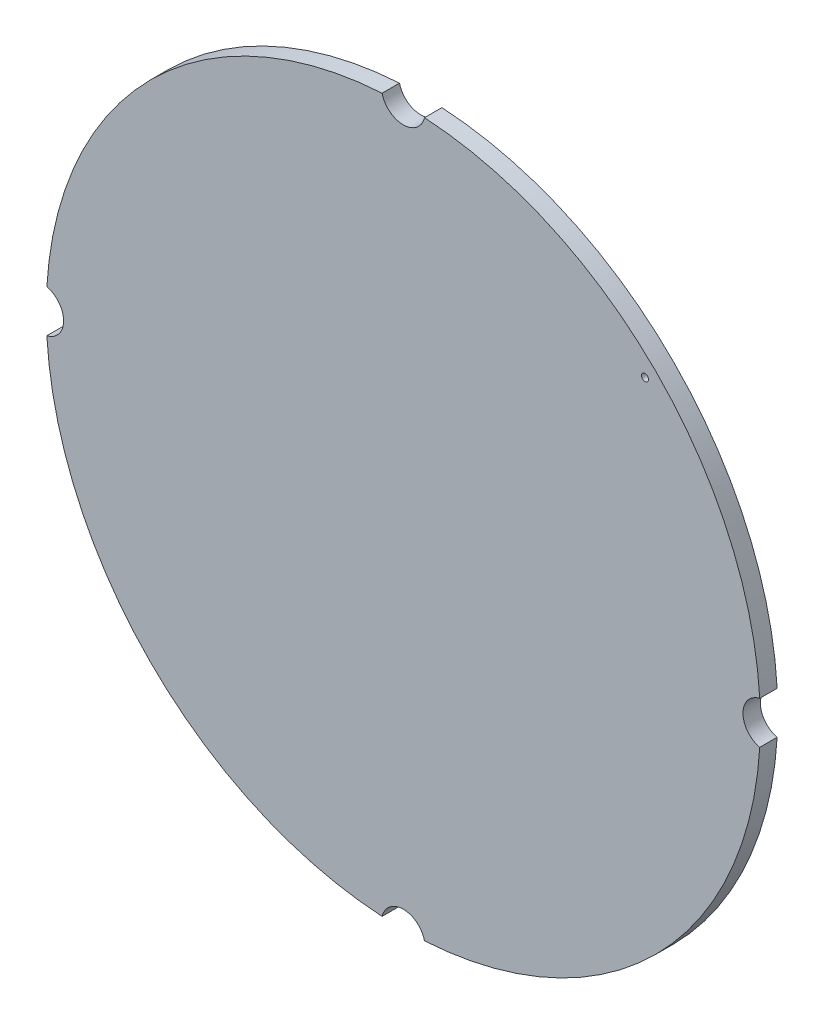
SolidWorks part; units mm, degrees
ref_plane "Front Plane" through (0, 0, 0) normal (0, 0, 1) x (1, 0, 0)
ref_plane "Top Plane" through (0, 0, 0) normal (0, 1, 0) x (1, 0, 0)
ref_plane "Right Plane" through (0, 0, 0) normal (1, 0, 0) x (0, 0, -1)
sketch "Sketch1" plane through (0, 0, 0) normal (0, 0, 1) x (1, 0, 0)
  circle A0 centre (0, 0) radius 75
  circle A1 centre (0, 0) radius 82
extrude "Boss-Extrude1" add sketch "Sketch1" along normal blind 3
sketch "Sketch2" plane through (0, 0, 3) normal (0, 0, 1) x (1, 0, 0)
  circle A0 centre (0, 0) radius 82
extrude "Boss-Extrude2" add sketch "Sketch2" along normal blind 1
sketch "Sketch3" plane through (0, 0, 0) normal (0, 1, 0) x (1, 0, 0)
  line L0 (0, -20.325) -> (0, 34.6526) construction
sketch "Sketch4" plane through (0, 0, 0) normal (0, 0, -1) x (-1, 0, 0)
  circle A0 centre (0, 83) radius 5
extrude "Cut-Extrude1" cut sketch "Sketch4" against normal through all
pattern_circular "CirPattern1" count 4 every 90 about axis through (0, 0, 0) along (0, 0, 1) of "Cut-Extrude1"
sketch "Sketch7" plane through (0, 0, 4) normal (0, 0, 1) x (1, 0, 0)
  circle A0 centre (55.5079, 55.5079) radius 0.7922
hole_wizard "M2x0.4 Tapped Hole1" positions "Sketch9" profile "Sketch8" tap size "M2x0.4" standard "ANSI Metric" end condition through all
sketch "Sketch9" plane through (0, 0, 4) normal (0, 0, 1) x (1, 0, 0)
  point P0 (55.5079, 55.5079)
cosmetic thread "Hole Thread1" parameters "D2"=2
sketch "Sketch8" plane through (55.5079, 55.5079, 4) normal (1, 0, 0) x (0, -1, 0)
  line L0 (0, 0) -> (0, 4)
  line L1 (0, 4) -> (0.8, 4)
  line L2 (0.8, 4) -> (0.8, 0)
  line L5 (0.8, 0) -> (0, 0)
  line L11 (0, -6.35) -> (0, 107.95) construction
  dimension "Thru Tap Drill Dia." = 1.6
  dimension "Thru Tap Drill Depth" = 4
